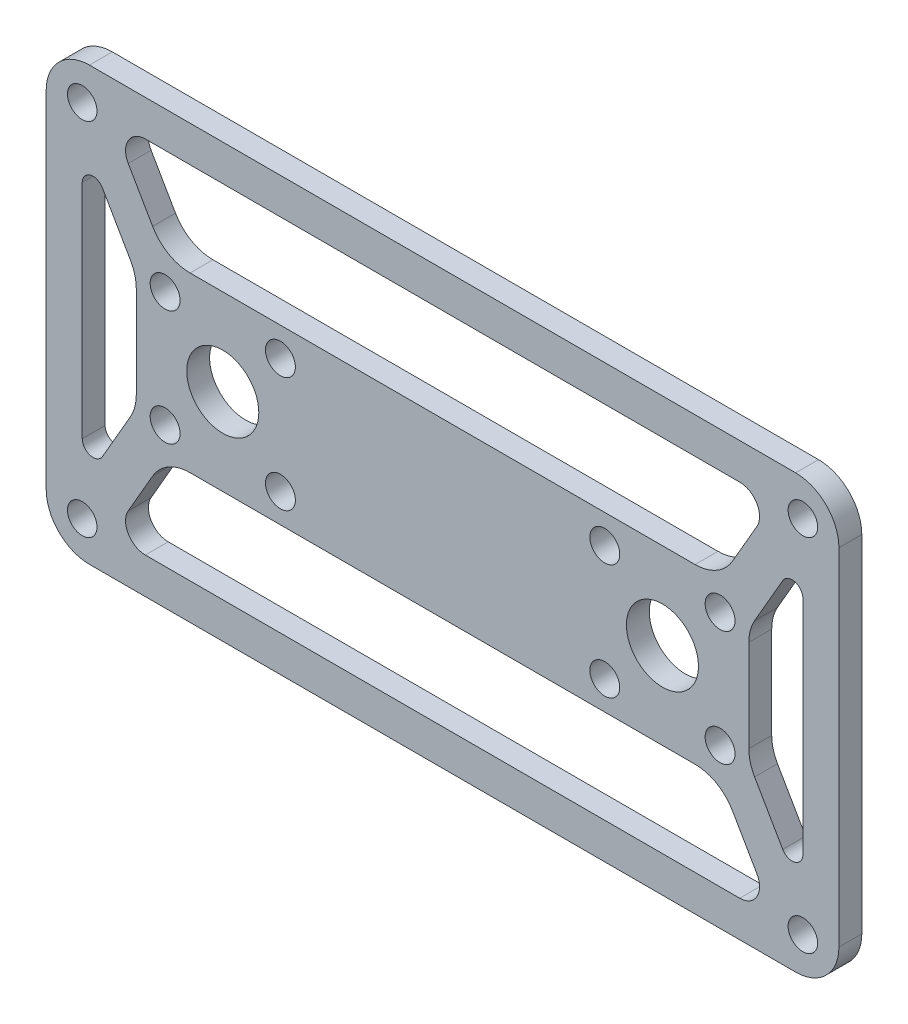
SolidWorks part; units mm, degrees
ref_plane "Front Plane" through (0, 0, 0) normal (0, 0, 1) x (1, 0, 0)
ref_plane "Top Plane" through (0, 0, 0) normal (0, 1, 0) x (1, 0, 0)
ref_plane "Right Plane" through (0, 0, 0) normal (1, 0, 0) x (0, 0, -1)
sketch "Sketch1" plane through (0, 0, 0) normal (0, 0, 1) x (1, 0, 0)
  line L0 (0, 0) -> (50000, 0) construction
  line L1 (50, 25) -> (-50, 25) construction
  line L2 (50, 25) -> (50, -25) construction
  line L3 (50, -25) -> (-50, -25) construction
  line L4 (-50, 25) -> (-50, -25) construction
  line L5 (50, 25) -> (-50, -25) construction
  line L6 (50, -25) -> (-50, 25) construction
  line L7 (55, -30) -> (-55, -30)
  line L8 (55, -30) -> (55, 30)
  line L9 (55, 30) -> (-55, 30)
  line L10 (-55, -30) -> (-55, 30)
  line L11 (55, -30) -> (-55, 30) construction
  line L12 (55, 30) -> (-55, -30) construction
  line L13 (-30.5, 0) -> (-55, 0) construction
  line L14 (-50, 21) -> (-50, -21)
  line L15 (-38.5, 8) -> (-22.5, 8) construction
  line L16 (-38.5, 8) -> (-38.5, -8) construction
  line L17 (-38.5, -8) -> (-22.5, -8) construction
  line L18 (-22.5, 8) -> (-22.5, -8) construction
  line L19 (-38.5, 8) -> (-22.5, -8) construction
  line L20 (-38.5, -8) -> (-22.5, 8) construction
  line L21 (22.51, 8) -> (38.51, 8) construction
  line L22 (22.51, 8) -> (22.51, -8) construction
  line L23 (22.51, -8) -> (38.51, -8) construction
  line L24 (38.51, 8) -> (38.51, -8) construction
  line L25 (22.51, 8) -> (38.51, -8) construction
  line L26 (22.51, -8) -> (38.51, 8) construction
  line L27 (-50, -21) -> (-42.5, -8)
  line L28 (-42.5, -8) -> (-42.5, 8)
  line L29 (-42.5, 8) -> (-50, 21)
  line L30 (0, 0) -> (0, -50000) construction
  line L31 (-22.5, -12) -> (-38.5, -12)
  line L32 (-38.5, -12) -> (-46, -25)
  line L33 (-46, -25) -> (46, -25)
  line L34 (-22.5, -12) -> (22.5, -12)
  line L35 (22.5, -12) -> (38.5, -12)
  line L36 (38.5, -12) -> (46, -25)
  line L37 (-22.5, 12) -> (-38.5, 12)
  line L38 (-38.5, 12) -> (-46, 25)
  line L39 (-46, 25) -> (46, 25)
  line L40 (38.5, 12) -> (46, 25)
  line L41 (22.5, 12) -> (38.5, 12)
  line L42 (-22.5, 12) -> (22.5, 12)
  line L43 (42.5, -8) -> (42.5, 8)
  line L44 (50, -21) -> (42.5, -8)
  line L45 (50, 21) -> (50, -21)
  line L46 (42.5, 8) -> (50, 21)
  circle A0 centre (-50, 25) radius 2.05
  circle A1 centre (50, 25) radius 2.05
  circle A2 centre (50, -25) radius 2.05
  circle A3 centre (-50, -25) radius 2.05
  circle A4 centre (-30.5, 0) radius 16 construction
  circle A5 centre (30.51, 0) radius 16 construction
  circle A6 centre (-38.5, 8) radius 2.075
  circle A7 centre (-22.5, 8) radius 2.075
  circle A8 centre (-22.5, -8) radius 2.075
  circle A9 centre (-38.5, -8) radius 2.075
  circle A10 centre (22.51, 8) radius 2.075
  circle A11 centre (38.51, 8) radius 2.075
  circle A12 centre (38.51, -8) radius 2.075
  circle A13 centre (22.51, -8) radius 2.075
  circle A14 centre (-30.5, 0) radius 5
  circle A15 centre (30.51, 0) radius 5
  circle A16 centre (-38.5, 8) radius 4 construction
  circle A17 centre (-22.5, 8) radius 4 construction
  circle A18 centre (-38.5, -8) radius 4 construction
  circle A19 centre (-22.5, -8) radius 4 construction
  circle A20 centre (22.51, -8) radius 4 construction
  circle A21 centre (22.51, 8) radius 4 construction
  circle A22 centre (38.51, 8) radius 4 construction
  circle A23 centre (38.51, -8) radius 4 construction
  circle A24 centre (50, 25) radius 4 construction
  circle A25 centre (50, -25) radius 4 construction
  circle A26 centre (-50, -25) radius 4 construction
  circle A27 centre (-50, 25) radius 4 construction
  point P0 (0, 0)
  point P6 (0, 0)
  point P64 (0, -12)
  point P66 (0, -25)
  dimension "D5" = 4.1
  dimension "D6" = 32
  dimension "D10" = 4.15
  dimension "D11" = 10
  dimension "D12" = 8
  dimension "D1" = 100
  dimension "D2" = 50
  dimension "D3" = 60
  dimension "D4" = 110
  dimension "D7" = 61.01
  dimension "D8" = 24.5
  dimension "D9" = 16
extrude "Boss-Extrude1" add sketch "Sketch1" along normal blind 3.175
fillet "Fillet1" radius 6 8 edges at (-42.5, -8, 1.5875) (-42.5, 8, 1.5875) (42.5, -8, 1.5875) (42.5, 8, 1.5875) (38.5, -12, 1.5875) (-38.5, -12, 1.5875) (38.5, 12, 1.5875) (-38.5, 12, 1.5875)
fillet "Fillet2" radius 2.75 4 edges at (46, -25, 1.5875) (-46, -25, 1.5875) (46, 25, 1.5875) (-46, 25, 1.5875)
fillet "Fillet3" radius 1.5 4 edges at (50, 21, 1.5875) (50, -21, 1.5875) (-50, -21, 1.5875) (-50, 21, 1.5875)
fillet "Fillet4" radius 6 4 edges at (55, 30, 1.5875) (55, -30, 1.5875) (-55, -30, 1.5875) (-55, 30, 1.5875)
